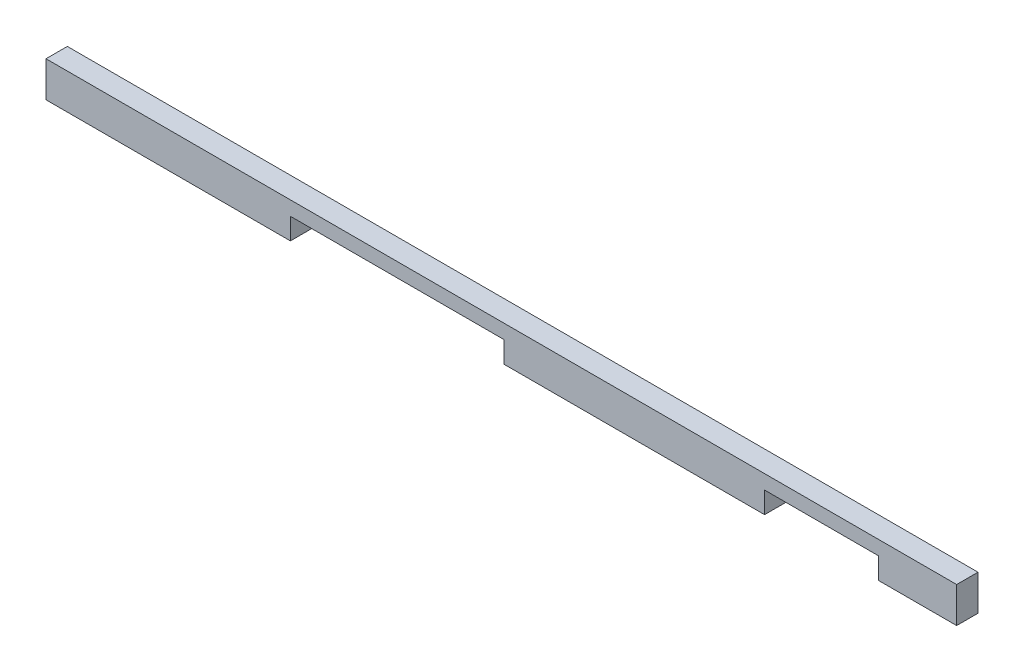
SolidWorks part; units mm, degrees
material "Pine"
ref_plane "Front Plane" through (0, 0, 0) normal (0, 0, 1) x (1, 0, 0)
ref_plane "Top Plane" through (0, 0, 0) normal (0, 1, 0) x (1, 0, 0)
ref_plane "Right Plane" through (0, 0, 0) normal (1, 0, 0) x (0, 0, -1)
sketch "Sketch1" plane through (0, 0, 0) normal (0, 1, 0) x (1, 0, 0)
  line L1 (-406.4, -9.525) -> (406.4, -9.525)
  line L2 (-406.4, -9.525) -> (-406.4, 9.525)
  line L3 (-406.4, 9.525) -> (406.4, 9.525)
  line L4 (406.4, -9.525) -> (406.4, 9.525)
  line L5 (-406.4, -9.525) -> (406.4, 9.525) construction
  line L6 (-406.4, 9.525) -> (406.4, -9.525) construction
  point P0 (0, 0)
  dimension "D1" = 19.05
  dimension "D2" = 812.8
extrude "Boss-Extrude1" add sketch "Sketch1" along normal blind 31.75
sketch "Sketch2" plane through (0, 0, -9.525) normal (0, 0, -1) x (-1, 0, 0)
  line L5 (-336.55, 0) -> (-234.95, 0)
  line L6 (-234.95, 0) -> (-234.95, 19.05)
  line L7 (-234.95, 19.05) -> (-336.55, 19.05)
  line L12 (-336.55, 19.05) -> (-336.55, 0)
  line L13 (-336.55, 0) -> (-234.95, 0)
  line L14 (-234.95, 0) -> (-234.95, 19.05)
  line L15 (-234.95, 19.05) -> (-336.55, 19.05)
  line L20 (-336.55, 19.05) -> (-336.55, 0)
  line L21 (-2.2355, 0) -> (188.2645, 0)
  line L22 (188.2645, 0) -> (188.2645, 19.05)
  line L23 (188.2645, 19.05) -> (-2.2355, 19.05)
  line L24 (-2.2355, 19.05) -> (-2.2355, 0)
  line L25 (-2.2355, 0) -> (188.2645, 0)
  line L26 (188.2645, 0) -> (188.2645, 19.05)
  line L27 (188.2645, 19.05) -> (-2.2355, 19.05)
  line L28 (-2.2355, 19.05) -> (-2.2355, 0)
  dimension "D1" = 0
  dimension "D2" = 0
extrude "Cut-Extrude1" cut sketch "Sketch2" against normal through all
